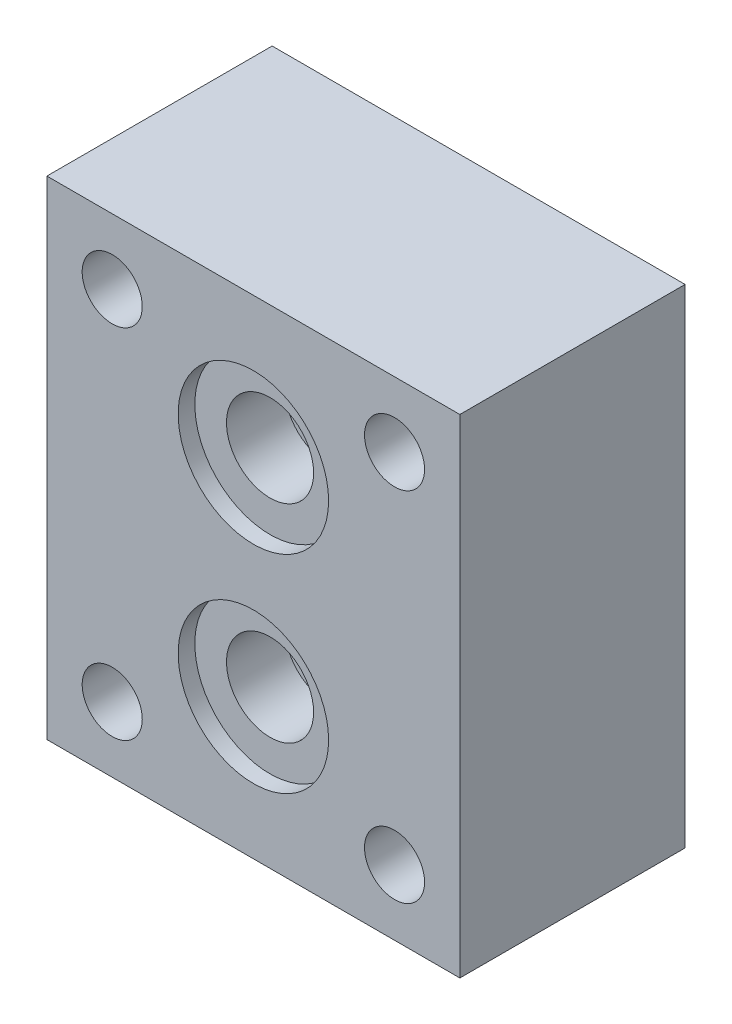
SolidWorks part; units mm, degrees
ref_plane "Front Plane" through (0, 0, 0) normal (1, 0, 0) x (0, 1, 0)
ref_plane "Top Plane" through (0, 0, 0) normal (0, 0, 1) x (0, 1, 0)
ref_plane "Right Plane" through (0, 0, 0) normal (0, 1, 0) x (-1, 0, 0)
sketch "Sketch1" plane through (0, 0, 0) normal (0, 0, 1) x (0, 1, 0)
  line L1 (-41.275, -34.925) -> (41.275, -34.925)
  line L2 (-41.275, -34.925) -> (-41.275, 34.925)
  line L3 (-41.275, 34.925) -> (41.275, 34.925)
  line L4 (41.275, -34.925) -> (41.275, 34.925)
  line L5 (-41.275, -34.925) -> (41.275, 34.925) construction
  line L6 (-41.275, 34.925) -> (41.275, -34.925) construction
  point P0 (0, 0)
  dimension "D1" = 41.275
  dimension "D2" = 34.925
extrude "Boss-Extrude1" add sketch "Sketch1" along normal mid plane 38.1
sketch "Sketch2" plane through (0, 0, 0) normal (0, 0, 1) x (0, 1, 0)
  circle A0 centre (-30.226, -23.876) radius 5.08
  circle A1 centre (30.226, -23.876) radius 5.08
  circle A2 centre (-30.226, 23.876) radius 5.08
  circle A3 centre (30.226, 23.876) radius 5.08
  point P8 (0, 0)
  dimension "D1" = 10.16
  dimension "D2" = 10.16
  dimension "D3" = 10.16
  dimension "D4" = 10.16
  dimension "D5" = 60.452
  dimension "D6" = 60.452
  dimension "D7" = 47.752
  dimension "D8" = 47.752
  dimension "D9" = 30.226
  dimension "D10" = 23.876
extrude "Cut-Extrude2" cut sketch "Sketch2" against normal through all from offset 19.05
sketch "Sketch3" plane through (0, 0, 0) normal (0, 0, 1) x (0, 1, 0)
  circle A0 centre (-17.526, 0) radius 7.366
  circle A1 centre (17.526, 0) radius 7.366
  point P4 (0, 0)
  dimension "D1" = 14.732
  dimension "D2" = 14.732
  dimension "D3" = 35.052
  dimension "D4" = 17.526
extrude "Cut-Extrude4" cut sketch "Sketch3" against normal blind 12.7 from offset 19.05
sketch "Sketch4" plane through (0, 0, 0) normal (0, 0, 1) x (0, 1, 0)
  circle A0 centre (-17.526, 0) radius 12.7254
  circle A1 centre (17.526, 0) radius 12.7254
  point P4 (0, 0)
  dimension "D1" = 25.4508
  dimension "D2" = 25.4508
  dimension "D3" = 35.052
  dimension "D4" = 17.526
extrude "Cut-Extrude6" cut sketch "Sketch4" against normal blind 2.8194 from offset 19.05
